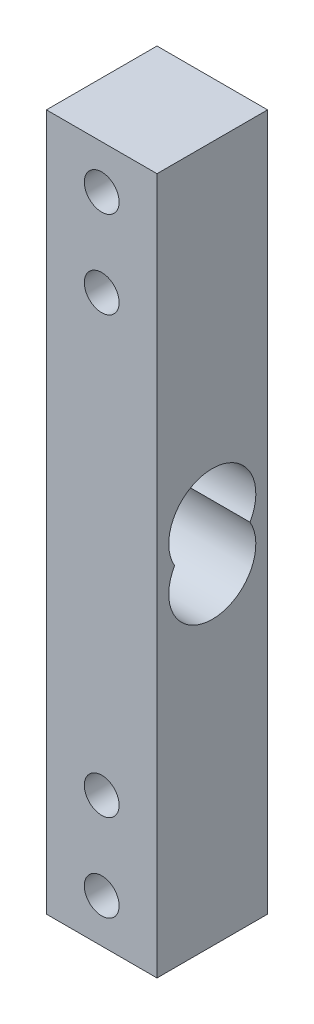
SolidWorks part; units mm, degrees
ref_plane "Front Plane" through (0, 0, 0) normal (0, 0, 1) x (1, 0, 0)
ref_plane "Top Plane" through (0, 0, 0) normal (0, 1, 0) x (1, 0, 0)
ref_plane "Right Plane" through (0, 0, 0) normal (1, 0, 0) x (0, 0, -1)
sketch "Sketch1" plane through (0, 0, 0) normal (0, 1, 0) x (1, 0, 0)
  line L1 (0, 0) -> (12.7, 0)
  line L2 (0, 0) -> (0, -12.7)
  line L3 (0, -12.7) -> (12.7, -12.7)
  line L4 (12.7, 0) -> (12.7, -12.7)
  dimension "D1" = 12.7
  dimension "D2" = 12.7
extrude "Boss-Extrude1" add sketch "Sketch1" along normal blind 80
sketch "Sketch2" plane through (12.7, 0, 0) normal (1, 0, 0) x (0, 0, -1)
  line L0 (-6.35, 80) -> (-6.35, 42.5) construction
  line L2 (-6.35, 37.5) -> (-6.35, 0) construction
  line L3 (-12.7, 40) -> (-6.35, 40) construction
  line L4 (-12.7, 80) -> (-12.7, 0) construction
  line L5 (0, 80) -> (0, 0) construction
  line L6 (-12.7, 80) -> (0, 80) construction
  line L7 (-12.7, 0) -> (0, 0) construction
  line L9 (-2.0199, 40) -> (0, 40) construction
  arc A1 (-10.6801, 40) -> (-2.0199, 40) centre (-6.35, 37.5) ccw
  arc A2 (-2.0199, 40) -> (-10.6801, 40) centre (-6.35, 42.5) ccw
  point P13 (-6.35, 32.5)
  dimension "D1" = 10
  dimension "D2" = 10
  dimension "D3" = 32.5
extrude "Cut-Extrude1" cut sketch "Sketch2" against normal blind 80
sketch "Sketch3" plane through (0, 0, 0) normal (0, 0, -1) x (-1, 0, 0)
  line L0 (-6.35, 80) -> (-6.35, 0) construction
  line L1 (-12.7, 80) -> (0, 80) construction
  line L2 (-12.7, 0) -> (0, 0) construction
  circle A0 centre (-6.35, 5) radius 2
  circle A1 centre (-6.35, 15) radius 2
  circle A2 centre (-6.35, 75) radius 2
  circle A3 centre (-6.35, 65) radius 2
  dimension "D1" = 4
  dimension "D2" = 4
  dimension "D3" = 4
  dimension "D4" = 4
  dimension "D5" = 5
  dimension "D6" = 5
  dimension "D7" = 15
  dimension "D8" = 15
extrude "Cut-Extrude2" cut sketch "Sketch3" against normal blind 80
